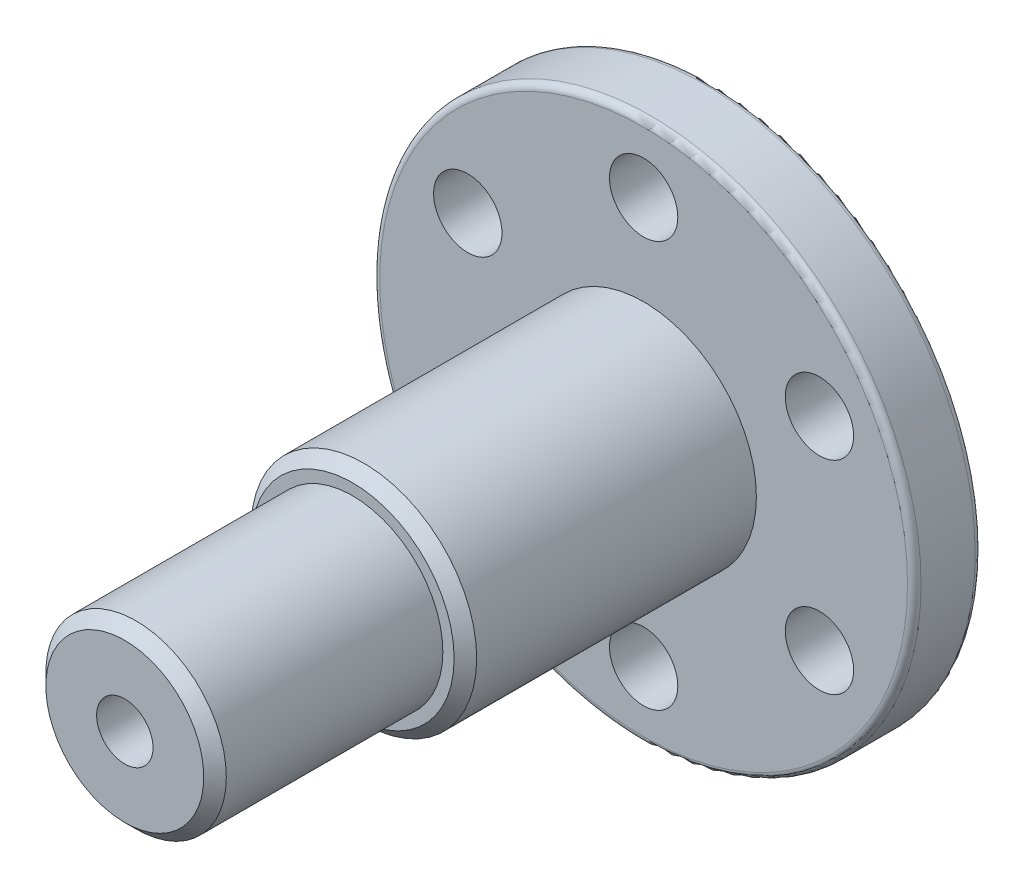
SolidWorks part; units mm, degrees
material "6061 合金"
ref_plane "前视基准面" through (0, 0, 0) normal (0, 0, 1) x (1, 0, 0)
ref_plane "上视基准面" through (0, 0, 0) normal (0, 1, 0) x (1, 0, 0)
ref_plane "右视基准面" through (0, 0, 0) normal (1, 0, 0) x (0, 0, -1)
sketch "草图1" plane through (0, 0, 0) normal (0, 0, 1) x (1, 0, 0)
  circle A0 centre (0, 0) radius 9 construction
  circle A1 centre (0, 9) radius 1.515
  circle A2 centre (7.7942, 4.5) radius 1.515
  circle A3 centre (7.7942, -4.5) radius 1.515
  circle A4 centre (0, -9) radius 1.515
  circle A5 centre (-7.7942, -4.5) radius 1.515
  circle A6 centre (-7.7942, 4.5) radius 1.515
  circle A9 centre (0, 0) radius 12
  point P21 (0, 0)
  dimension "D1" = 18
  dimension "D2" = 3.03
  dimension "D4" = 3
  dimension "D3" = 6
extrude "凸台-拉伸1" add sketch "草图1" along normal blind 3
sketch "草图2" plane through (0, 0, 3) normal (0, 0, 1) x (1, 0, 0)
  circle A0 centre (0, 0) radius 5
  dimension "D1" = 10
extrude "凸台-拉伸2" add sketch "草图2" along normal blind 23
sketch "草图3" plane through (0, 0, 26) normal (0, 0, 1) x (1, 0, 0)
  circle A0 centre (0, 0) radius 4
  dimension "D1" = 8
extrude "切除-拉伸1" cut sketch "草图3" against normal offset from surface (10.1 mm away) 12.9 flip side to cut up to face at (5, 0, 3)
chamfer "倒角1" distance 0.5 angle 45 2 edges at (5, 0, 15.9) (4, 0, 26)
fillet "圆角1" radius 0.3 2 edges at (12, 0, 0) (12, 0, 3)
hole_wizard "M3 螺纹孔1" positions "草图4" profile "草图5" tap size "M3" standard "GB"
sketch "草图4" plane through (0, 0, 26) normal (0, 0, 1) x (1, 0, 0)
  point P0 (0, 0)
sketch "草图5" plane through (0, 0, 26) normal (1, 0, 0) x (0, -1, 0)
  line L0 (0, 0) -> (0, 10.2511)
  line L1 (0, 10.2511) -> (1.25, 9.5)
  line L2 (1.25, 9.5) -> (1.25, 0)
  line L5 (1.25, 0) -> (0, 0)
  line L10 (0, 10.2511) -> (-1.25, 9.5) construction
  line L11 (0, -6.35) -> (0, 107.95) construction
  dimension "螺纹孔钻头直径" = 2.5
  dimension "螺纹孔钻头深度" = 9.5
  dimension "导头角度" = 118
cosmetic thread "孔螺蚊线1" parameters "D1"=8, "D2"=3
